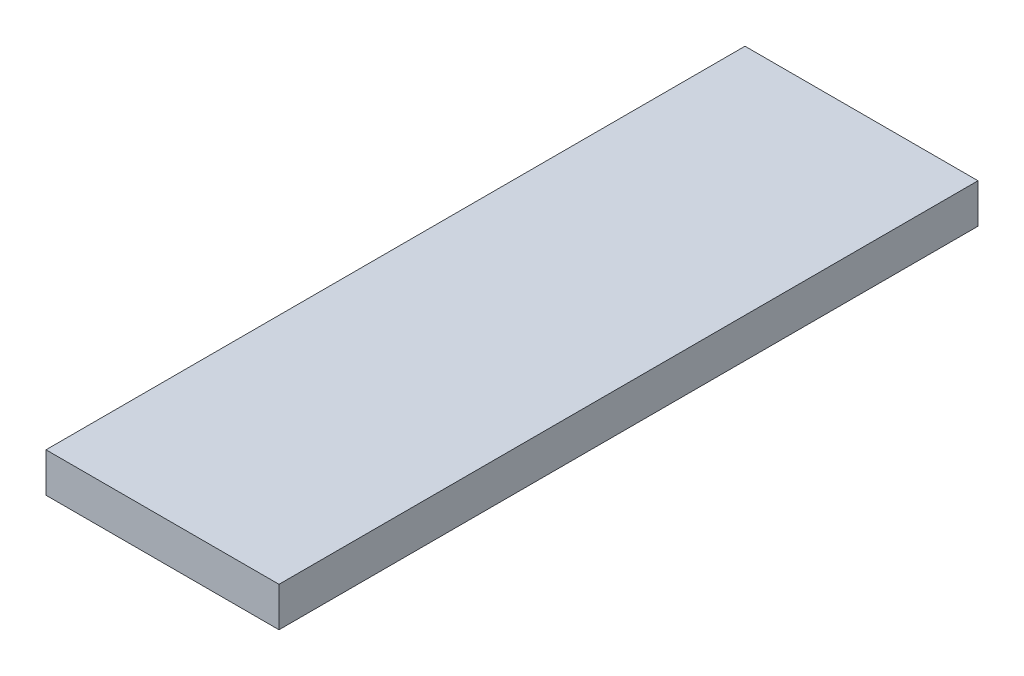
SolidWorks part; units mm, degrees
ref_plane "Front Plane" through (0, 0, 0) normal (0, 0, 1) x (1, 0, 0)
ref_plane "Top Plane" through (0, 0, 0) normal (0, 1, 0) x (1, 0, 0)
ref_plane "Right Plane" through (0, 0, 0) normal (1, 0, 0) x (0, 0, -1)
sketch "Sketch1" plane through (0, 0, 0) normal (0, 1, 0) x (1, 0, 0)
  line L1 (0, 0) -> (55, 0)
  line L2 (0, 0) -> (0, 165)
  line L3 (0, 165) -> (55, 165)
  line L4 (55, 0) -> (55, 165)
  dimension "D1" = 55
  dimension "D2" = 165
extrude "Boss-Extrude1" add sketch "Sketch1" along normal blind 9.3
